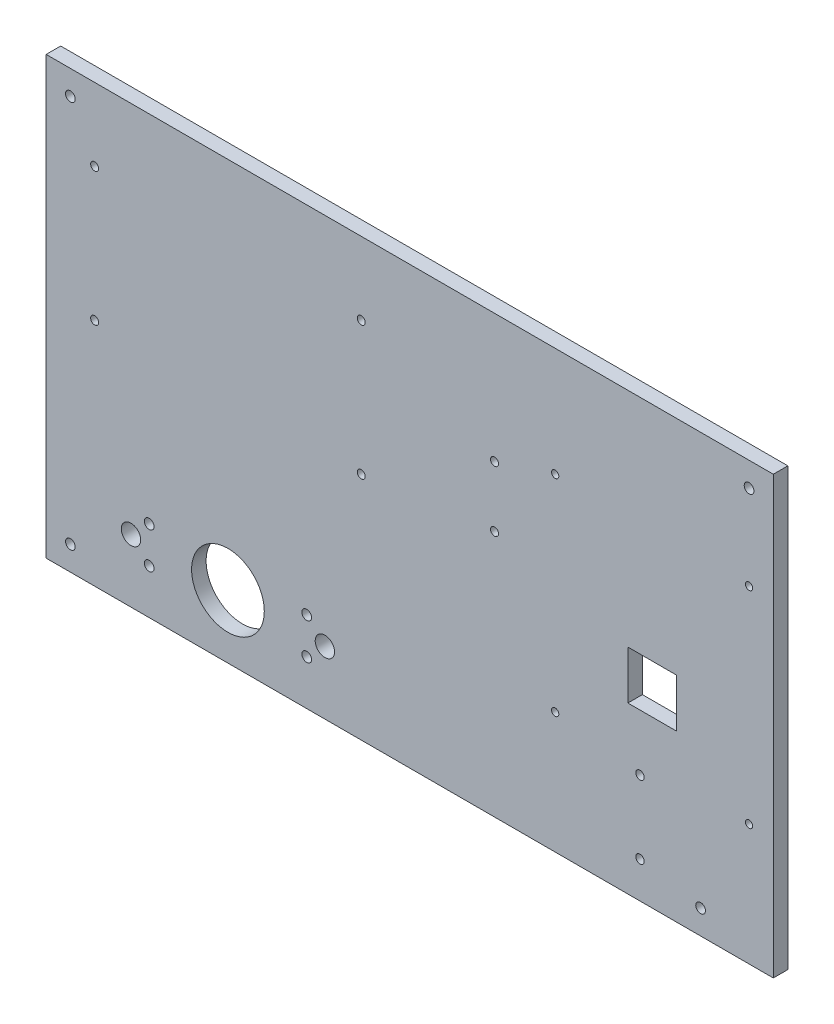
SolidWorks part; units mm, degrees
material "Faia"
ref_plane "Plano frontal" through (0, 0, 0) normal (0, 0, 1) x (1, 0, 0)
ref_plane "Plano superior" through (0, 0, 0) normal (0, 1, 0) x (1, 0, 0)
ref_plane "Plano direito" through (0, 0, 0) normal (1, 0, 0) x (0, 0, -1)
sketch "Esboço1" plane through (0, 0, 0) normal (0, 0, 1) x (1, 0, 0)
  line L0 (150, 0) -> (-150, 0) construction
  line L1 (-150, 90) -> (150, 90)
  line L2 (-150, 90) -> (-150, -90)
  line L3 (-150, -90) -> (150, -90)
  line L4 (150, 90) -> (150, -90)
  line L5 (-150, 90) -> (150, -90) construction
  line L6 (-150, -90) -> (150, 90) construction
  line L7 (70, 0) -> (-230, 0) construction
  line L8 (-83.2276, -64) -> (-64.3617, -64) construction
  line L9 (60, 45) -> (60, -40) construction
  line L10 (140, 45) -> (60, 45) construction
  line L11 (60, -40) -> (140, -40) construction
  line L12 (-75, -58.1086) -> (-75, -85.356) construction
  line L13 (90, -1.75) -> (110, -1.75)
  line L14 (90, -1.75) -> (90, -21.75)
  line L15 (90, -21.75) -> (110, -21.75)
  line L16 (110, -1.75) -> (110, -21.75)
  line L17 (90, -1.75) -> (110, -21.75) construction
  line L18 (90, -21.75) -> (110, -1.75) construction
  line L19 (100, -11.75) -> (100, -4.0979) construction
  line L20 (-20, 5) -> (-130, 5) construction
  line L21 (-20, 5) -> (-20, 60) construction
  line L22 (-20, 60) -> (-130, 60) construction
  line L23 (-130, 5) -> (-130, 60) construction
  line L24 (-20, 5) -> (-130, 60) construction
  line L25 (-20, 60) -> (-130, 5) construction
  circle A0 centre (140, 45) radius 1.5
  circle A1 centre (140, -40) radius 1.5
  circle A2 centre (60, -40) radius 1.5
  circle A3 centre (60, 45) radius 1.5
  circle A4 centre (-107.5, -56.5) radius 2
  circle A5 centre (-42.5, -56.5) radius 2
  circle A6 centre (-75, -64) radius 15
  circle A7 centre (-35, -64) radius 4
  circle A8 centre (-115, -64) radius 4
  circle A9 centre (-42.5, -71.5) radius 2
  circle A10 centre (-107.5, -71.5) radius 2
  circle A11 centre (35, 37) radius 1.65
  circle A12 centre (35, 12) radius 1.65
  circle A13 centre (-130, 60) radius 1.65
  circle A14 centre (-20, 60) radius 1.65
  circle A15 centre (-20, 5) radius 1.65
  circle A16 centre (-130, 5) radius 1.65
  circle A17 centre (95, -45) radius 1.75
  circle A20 centre (95, -75) radius 1.75
  point P0 (0, 0)
  point P21 (5, 0)
  point P23 (100, -11.75)
  point P28 (100, -40)
  point P48 (-75, 32.5)
  point P58 (0, 0)
  dimension "D5" = 3
  dimension "D8" = 32.5
  dimension "D16" = 30
  dimension "D19" = 8
  dimension "D20" = 80
  dimension "D10" = 4
  dimension "D21" = 3.3
  dimension "D26" = 3.3
  dimension "D29" = 30
  dimension "D30" = 3.5
  dimension "D1" = 300
  dimension "D2" = 180
  dimension "D3" = 10
  dimension "D4" = 85
  dimension "D7" = 80
  dimension "D9" = 15
  dimension "D11" = 25
  dimension "D12" = 50
  dimension "D13" = 20
  dimension "D14" = 20
  dimension "D15" = 28.25
  dimension "D17" = 75
  dimension "D18" = 26
  dimension "D22" = 25
  dimension "D23" = 8
  dimension "D24" = 55
  dimension "D25" = 110
  dimension "D27" = 30
  dimension "D28" = 20
  dimension "D31" = 55
  dimension "D32" = 15
  dimension "D6" = 2
extrude "Ressalto-extrusão1" add sketch "Esboço1" along normal blind 6 contours L4 L1 L2 L3 A3 A1 A0 A2
sketch "Esboço2" plane through (0, 0, 6) normal (0, 0, 1) x (1, 0, 0)
  line L0 (150, 0) -> (-150, 0) construction
  line L1 (-150, 90) -> (150, 90)
  line L2 (-150, 90) -> (-150, -90)
  line L3 (-150, -90) -> (150, -90)
  line L4 (150, 90) -> (150, -90)
  line L5 (-150, 90) -> (150, -90) construction
  line L6 (-150, -90) -> (150, 90) construction
  line L7 (140, 80) -> (140, 90) construction
  line L8 (120, -80) -> (120, -90) construction
  circle A0 centre (120, -80) radius 2
  circle A1 centre (140, 80) radius 2
  circle A2 centre (-140, 80) radius 2
  circle A3 centre (-140, -80) radius 2
  point P0 (0, 0)
  point P16 (0.5357, 0)
  dimension "D3" = 4
  dimension "D1" = 300
  dimension "D2" = 180
  dimension "D4" = 10
  dimension "D5" = 30
  dimension "D6" = 10
  dimension "D7" = 10
extrude "Corte-extrusão1" cut sketch "Esboço2" against normal blind 10 contours A2 | A1 | A0 | A3
